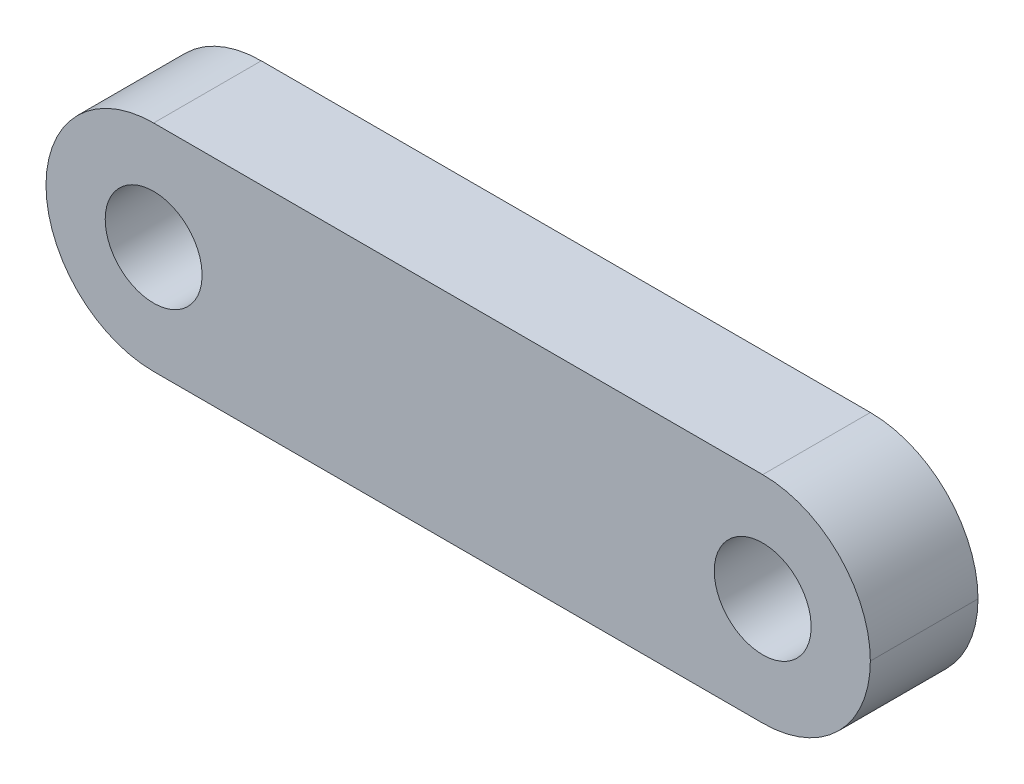
SolidWorks part; units mm, degrees
ref_plane "前视基准面" through (0, 0, 0) normal (0, 0, 1) x (1, 0, 0)
ref_plane "上视基准面" through (0, 0, 0) normal (0, 1, 0) x (1, 0, 0)
ref_plane "右视基准面" through (0, 0, 0) normal (1, 0, 0) x (0, 0, -1)
ref_plane "基准面1" through (0, 0, 3) normal (0, 0, 1) x (1, 0, 0)
sketch "草图1" plane through (0, 0, 3) normal (0, 0, 1) x (1, 0, 0)
  line L0 (-9.2001, 0) -> (7.7741, 0)
  line L1 (7.7741, 5.999) -> (-9.2001, 5.999)
  circle A0 centre (-9.2001, 3) radius 1.35
  circle A1 centre (7.7741, 3) radius 1.35
  arc A2 (-9.2001, 5.999) -> (-12.2001, 2.999) centre (-9.2001, 2.999) ccw
  arc A3 (-12.2001, 2.999) -> (-9.2001, 0) centre (-9.2001, 3) ccw
  arc A4 (7.7741, 0) -> (10.7741, 3) centre (7.7741, 3) ccw
  arc A5 (10.7741, 3) -> (7.7741, 5.999) centre (7.7741, 2.999) ccw
extrude "凸台-拉伸1" add sketch "草图1" against normal blind 3
